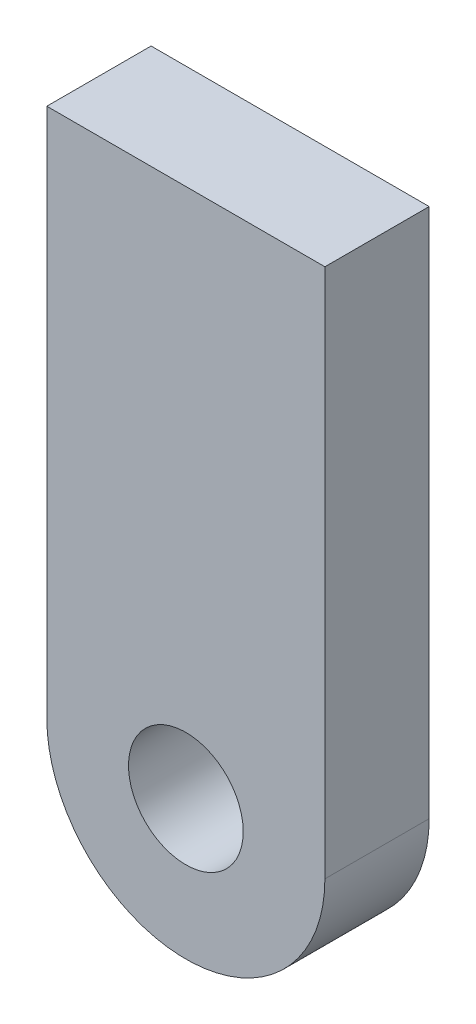
SolidWorks part; units mm, degrees
ref_plane "前视基准面" through (0, 0, 0) normal (0, 0, 1) x (1, 0, 0)
ref_plane "上视基准面" through (0, 0, 0) normal (0, 1, 0) x (1, 0, 0)
ref_plane "右视基准面" through (0, 0, 0) normal (1, 0, 0) x (0, 0, -1)
sketch "草图1" plane through (0, 0, 0) normal (0, 0, 1) x (1, 0, 0)
  line L0 (-4, 0) -> (-4, 15.25)
  line L1 (-4, 15.25) -> (4, 15.25)
  line L2 (0, 15.25) -> (0, 0) construction
  line L3 (4, 0) -> (4, 15.25)
  circle A0 centre (0, 0) radius 1.65
  arc A1 (-4, 0) -> (4, 0) centre (0, 0) ccw
  dimension "D1" = 3.3
  dimension "D2" = 8
  dimension "D3" = 15.25
  dimension "D4" = 8
extrude "凸台-拉伸1" add sketch "草图1" along normal blind 3
